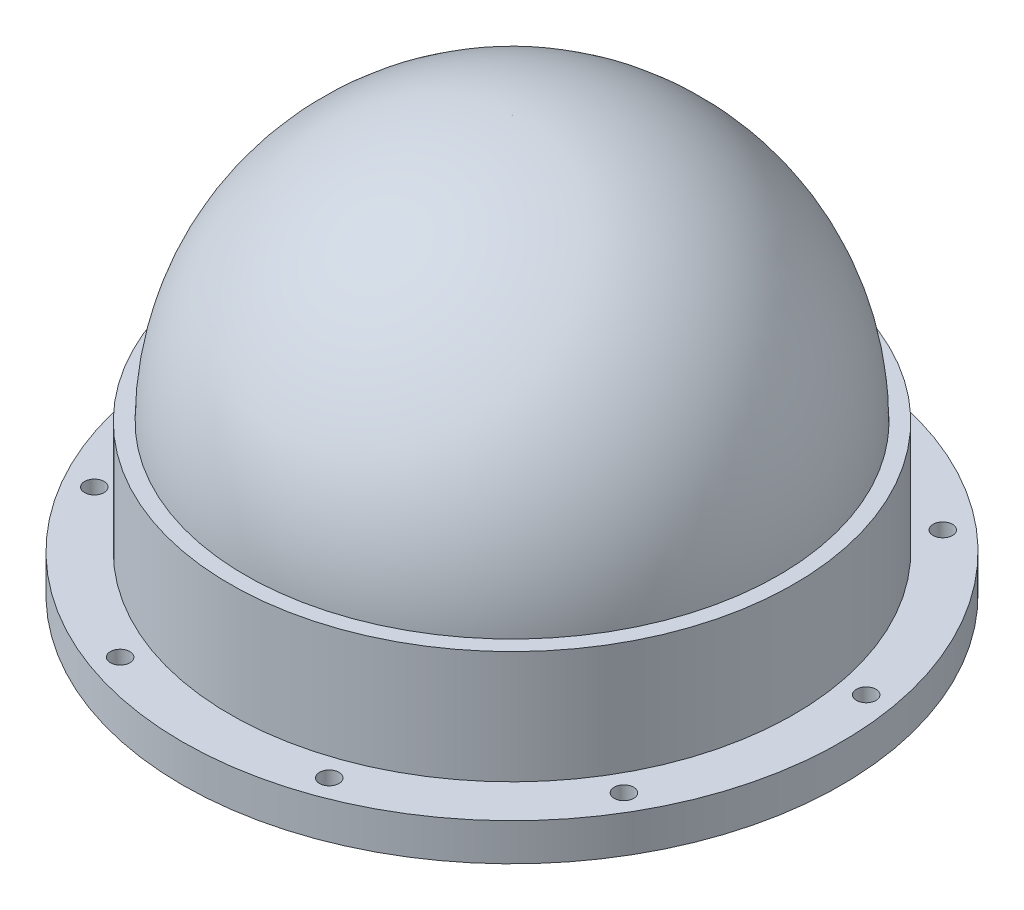
SolidWorks part; units mm, degrees
material "AISI 304"
ref_plane "Front" through (0, 0, 0) normal (0, 0, 1) x (1, 0, 0)
ref_plane "Top" through (0, 0, 0) normal (0, 1, 0) x (1, 0, 0)
ref_plane "Right" through (0, 0, 0) normal (1, 0, 0) x (0, 0, -1)
sketch "Sketch1" plane through (0, 0, 0) normal (0, 0, 1) x (1, 0, 0)
  line L0 (0, 0) -> (0, 136.398) construction
  line L1 (79.248, 0) -> (79.248, 36.83)
  line L2 (79.248, 0) -> (114.3, 0)
  line L3 (114.3, 0) -> (114.3, 12.954)
  line L4 (114.3, 12.954) -> (97.79, 12.954)
  line L5 (97.79, 12.954) -> (97.79, 52.07)
  line L6 (97.79, 52.07) -> (92.456, 52.07)
  line L7 (92.456, 52.07) -> (92.456, 36.83)
  line L8 (92.456, 36.83) -> (79.248, 36.83)
  line L9 (80.01, 56.388) -> (80.01, 36.83) construction
  line L10 (0, 144.018) -> (0, 136.398) construction
  arc A0 (0, 136.398) -> (80.01, 56.388) centre (0, 56.388) cw construction
  arc A1 (0, 144.018) -> (92.456, 51.562) centre (0, 51.562) cw construction
  dimension "D6" = 136.398
  dimension "D7" = 80.01
  dimension "D9" = 7.62
  dimension "D1" = 158.496
  dimension "D2" = 228.6
  dimension "D3" = 195.58
  dimension "D4" = 12.954
  dimension "D5" = 52.07
  dimension "D8" = 12.446
  dimension "D10" = 15.24
revolve "Revolve1" add sketch "Sketch1" angle 360 about L0
sketch "Sketch2" plane through (0, 0, 0) normal (0, 0, 1) x (1, 0, 0)
  line L0 (80.01, 56.388) -> (80.01, 36.83) construction
  line L1 (80.01, 56.388) -> (80.01, 36.83)
  line L2 (92.456, 51.562) -> (92.456, 36.83)
  line L3 (92.456, 36.83) -> (80.01, 36.83)
  line L4 (0, 144.018) -> (0, 136.398) construction
  line L5 (0, 144.018) -> (0, 136.398)
  arc A0 (92.456, 51.562) -> (0, 144.018) centre (0, 51.562) ccw construction
  arc A1 (80.01, 56.388) -> (0, 136.398) centre (0, 56.388) ccw construction
  arc A2 (92.456, 51.562) -> (0, 144.018) centre (0, 51.562) ccw
  arc A3 (80.01, 56.388) -> (0, 136.398) centre (0, 56.388) ccw
revolve "Revolve2" add sketch "Sketch2" angle 360 about L4
hole_wizard "1/4 Clearance Hole1" positions "Sketch3" profile "Sketch4" hole size "1/4" standard "ANSI Inch" end condition up to next
sketch "Sketch3" plane through (0, 12.954, 0) normal (0, 1, 0) x (1, 0, 0)
  line L0 (0, 0) -> (0, 106.045) construction
  point P0 (0, 106.045)
  point P5 (68.1644, 81.2352)
  point P6 (104.4339, 18.4145)
  point P7 (91.8377, -53.0225)
  point P8 (36.2695, -99.6497)
  point P9 (-36.2695, -99.6497)
  point P10 (-91.8377, -53.0225)
  point P11 (-104.4339, 18.4145)
  point P12 (-68.1644, 81.2352)
  dimension "D2" = 106.045
  dimension "D1" = 9
sketch "Sketch4" plane through (0, 12.954, -106.045) normal (1, 0, 0) x (0, 0, 1)
  line L0 (0, 0) -> (0, 12.954)
  line L1 (0, 12.954) -> (3.3782, 12.954)
  line L2 (3.3782, 12.954) -> (3.3782, 0)
  line L5 (3.3782, 0) -> (0, 0)
  line L11 (0, -6.35) -> (0, 107.95) construction
  dimension "Thru Hole Dia." = 6.7564
  dimension "Thru Hole Depth" = 12.954
ref_plane "Plane1" through (0, 0, 0) normal (1, 0, 0) x (0, 0, -1)
sketch "Sketch5" plane through (0, 0, 0) normal (1, 0, 0) x (0, 0, -1)
  line L0 (0, 144.018) -> (0, 143.018)
  line L2 (0, 144.018) -> (0.1, 144.018)
  line L3 (0, 144.018) -> (0, 143.018)
  line L4 (0, 143.018) -> (0.1, 143.018)
  line L5 (0.1, 144.018) -> (0.1, 143.018)
  line L6 (0, 143.018) -> (-0.1, 143.018)
  line L7 (0, 143.018) -> (0, 144.0179)
  line L8 (0, 144.0179) -> (-0.1, 144.0179)
  line L9 (-0.1, 143.018) -> (-0.1, 144.0179)
  arc A0 (92.456, 51.562) -> (-92.456, 51.562) centre (0, 51.562) ccw construction
  dimension "D1" = 1
  dimension "D2" = 0.1
  dimension "D3" = 0.1
extrude "Boss-Extrude1" add sketch "Sketch5" along normal blind 0.1 contours L9 L6 L3 L8 | L5 L2 L0 L3 L4
